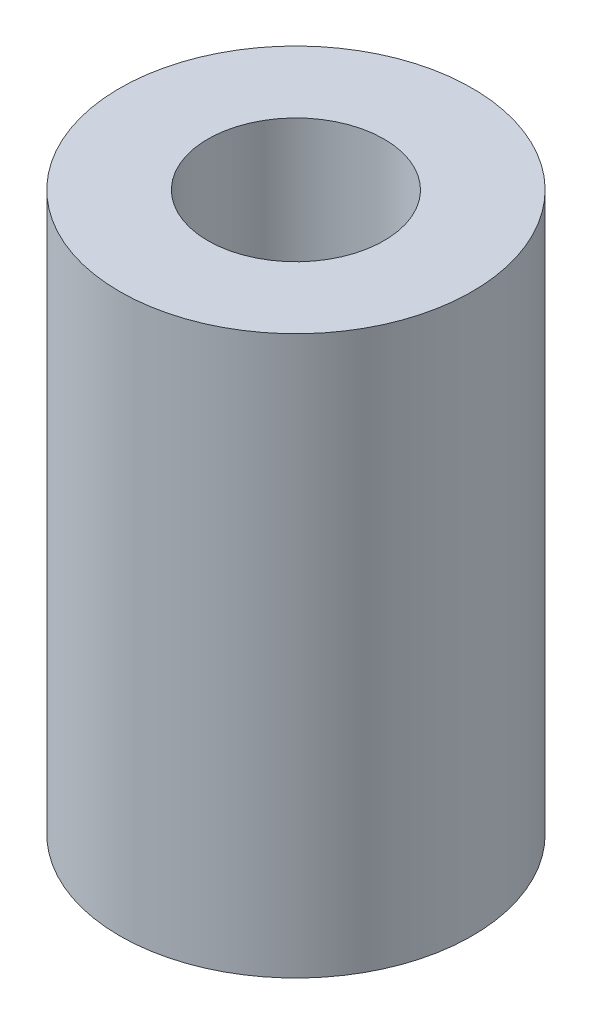
SolidWorks part; units mm, degrees
material "6061-O (SS)"
ref_plane "Front Plane" through (0, 0, 0) normal (0, 0, 1) x (1, 0, 0)
ref_plane "Top Plane" through (0, 0, 0) normal (0, 1, 0) x (1, 0, 0)
ref_plane "Right Plane" through (0, 0, 0) normal (1, 0, 0) x (0, 0, -1)
sketch "Sketch1" plane through (0, 0, 0) normal (0, 1, 0) x (1, 0, 0)
  circle A0 centre (0, 0) radius 3
  circle A1 centre (0, 0) radius 6
  dimension "D1" = 6
  dimension "D2" = 12
extrude "Boss-Extrude1" add sketch "Sketch1" along normal blind 19
